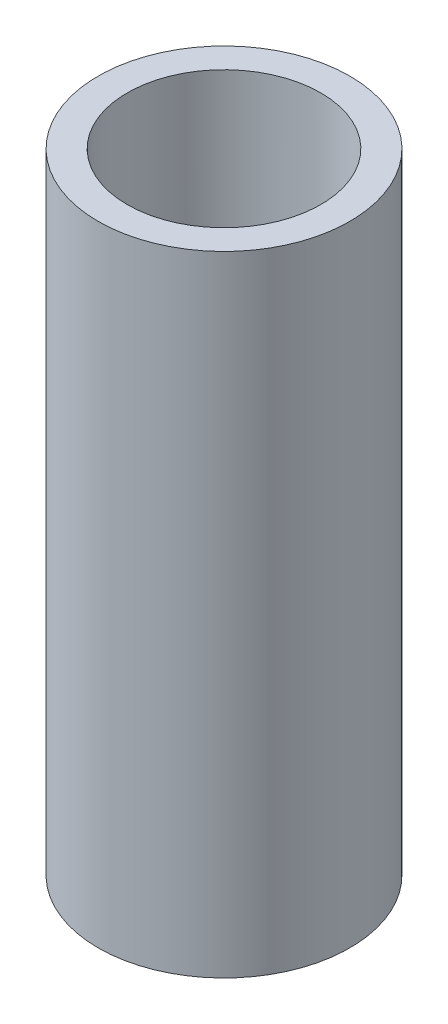
SolidWorks part; units mm, degrees
ref_plane "Front Plane" through (0, 0, 0) normal (0, 0, 1) x (1, 0, 0)
ref_plane "Top Plane" through (0, 0, 0) normal (0, 1, 0) x (1, 0, 0)
ref_plane "Right Plane" through (0, 0, 0) normal (1, 0, 0) x (0, 0, -1)
sketch "Buitencirkel" plane through (0, 0, 0) normal (0, 1, 0) x (1, 0, 0)
  circle A1 centre (0, 0) radius 13
  dimension "D2" = 26
extrude "Cilinder basis" add sketch "Buitencirkel" along normal blind 65
ref_plane "Plane2" through (0, 0, 0) normal (0, -1, 0) x (-1, 0, 0)
sketch "Binnencirkel motor" plane through (0, 0, 0) normal (0, -1, 0) x (-1, 0, 0)
  circle A0 centre (0, 0) radius 11
  dimension "D1" = 22
extrude "Holte motor" cut sketch "Binnencirkel motor" against normal blind 25
ref_plane "Plane3" through (0, 65, 0) normal (0, 1, 0) x (1, 0, 0)
sketch "Binnencirkel buis" plane through (0, 65, 0) normal (0, 1, 0) x (1, 0, 0)
  circle A0 centre (0, 0) radius 10
  dimension "D1" = 20
extrude "Holte buis" cut sketch "Binnencirkel buis" against normal blind 35
ref_plane "Plane4" through (0, 25, 0) normal (0, -1, 0) x (-1, 0, 0)
sketch "Cirkel motoras" plane through (0, 25, 0) normal (0, -1, 0) x (-1, 0, 0)
  line L0 (0, 2.85) -> (0, -2.85) construction
  line L1 (-11, 0) -> (11, 0) construction
  line L2 (2.35, -1.6125) -> (2.35, 1.6125)
  circle A0 centre (0, 0) radius 11 construction
  arc A1 (2.35, 1.6125) -> (2.35, -1.6125) centre (0, 0) ccw
  point P9 (0, 0)
  point P13 (0, 0)
  dimension "D1" = 5.7
  dimension "D2" = 2.35
extrude "Uitsparing motoras" cut sketch "Cirkel motoras" against normal through all contours A1 L2
sketch "Cirkel motorpinnetjes" plane through (0, 25, 0) normal (0, -1, 0) x (-1, 0, 0)
  line L0 (0, 2.85) -> (0, -2.85) construction
  line L1 (-5.5, 0) -> (5.5, 0) construction
  circle A0 centre (-5.5, 0) radius 0.9
  arc A1 (2.35, 1.6125) -> (2.35, -1.6125) centre (0, 0) ccw construction
  circle A2 centre (0, 0) radius 5.5 construction
  circle A3 centre (5.5, 0) radius 0.9
  point P10 (0, 0)
  point P14 (0, 0)
  dimension "D1" = 1.8
  dimension "D2" = 11
extrude "Uitsparingen motorpinnetjes" add sketch "Cirkel motorpinnetjes" along normal blind 2
sketch "Cirkel polen" plane through (0, 25, 0) normal (0, -1, 0) x (-1, 0, 0)
  line L0 (0, 0) -> (0, -11) construction
  line L1 (0, 0) -> (11, 0) construction
  circle A0 centre (0, 0) radius 11 construction
  circle A2 centre (0, -7.55) radius 2.45
  circle A3 centre (0, 7.55) radius 2.45
  circle A4 centre (0, 0) radius 10 construction
  dimension "D1" = 4.9
extrude "Uitsparingen motorpolen" cut sketch "Cirkel polen" against normal through all contours A3 | A2
